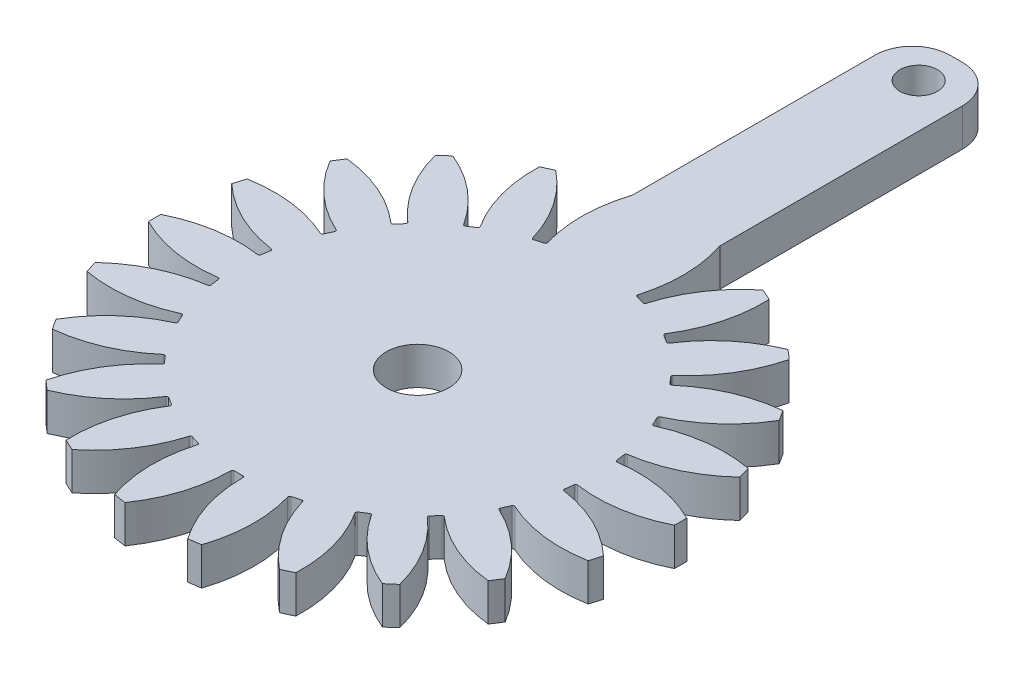
SolidWorks part; units mm, degrees
material "Copper"
ref_plane "Front Plane" through (0, 0, 0) normal (0, 0, 1) x (1, 0, 0)
ref_plane "Top Plane" through (0, 0, 0) normal (0, 1, 0) x (1, 0, 0)
ref_plane "Right Plane" through (0, 0, 0) normal (1, 0, 0) x (0, 0, -1)
sketch "Sketch1" plane through (0, 0, 0) normal (0, 1, 0) x (1, 0, 0)
  circle A0 centre (0, 0) radius 21
  dimension "D1" = 42
extrude "Boss-Extrude1" add sketch "Sketch1" along normal blind 3
sketch "Sketch2" plane through (0, 3, 0) normal (0, 1, 0) x (1, 0, 0)
  circle A0 centre (0, 0) radius 2.5
  dimension "D1" = 5
extrude "Cut-Extrude1" cut sketch "Sketch2" against normal through all both and the other way through all
sketch "Sketch3" plane through (0, 3, 0) normal (0, 1, 0) x (1, 0, 0)
  line L0 (0, 0) -> (0, 21) construction
  line L1 (0.35, 14.3) -> (-0.35, 14.3)
  circle A0 centre (0, 0) radius 21 construction
  arc A3 (-2.5, 20.8507) -> (2.5, 20.8507) centre (0, 0) cw
  arc A6 (-0.35, 14.3) -> (-0.4765, 14.4265) centre (-0.35, 14.4265) cw
  arc A7 (-0.4765, 14.4265) -> (-2.5, 20.8507) centre (-11.6858, 14.4265) ccw
  arc A8 (0.35, 14.3) -> (0.4765, 14.4265) centre (0.35, 14.4265) ccw
  arc A9 (0.4765, 14.4265) -> (2.5, 20.8507) centre (11.6858, 14.4265) cw
  point P21 (0, 21)
  point P22 (0, 14.3)
  dimension "D4" = 6.7
  dimension "D1" = 5
  dimension "D2" = 0.7
extrude "Cut-Extrude2" cut sketch "Sketch3" against normal through all both and the other way through all
pattern_circular "CirPattern1" count 22 over 360 about axis through (0, 0, 0) along (0, 1, 0) of "Cut-Extrude2"
sketch "Sketch4" plane through (0, 3, 0) normal (0, 1, 0) x (1, 0, 0)
  line L0 (0, 27.75) -> (0, 0) construction
  line L1 (-3.5, 43) -> (3.5, 43)
  line L2 (-3.5, 43) -> (-3.5, 12.5)
  line L3 (-3.5, 12.5) -> (3.5, 12.5)
  line L4 (3.5, 43) -> (3.5, 12.5)
  line L5 (-3.5, 43) -> (3.5, 12.5) construction
  line L6 (-3.5, 12.5) -> (3.5, 43) construction
  point P0 (0, 27.75)
  dimension "D1" = 7
  dimension "D2" = 30.5
  dimension "D3" = 12.5
extrude "Boss-Extrude2" add sketch "Sketch4" against normal blind 3
fillet "Fillet1" radius 3 2 edges at (3.5, 1.5, -43) (-3.5, 1.5, -43)
sketch "Sketch5" plane through (0, 3, 0) normal (0, 1, 0) x (1, 0, 0)
  line L0 (0, 43) -> (0, 40) construction
  line L1 (0.5, 43) -> (-0.5, 43) construction
  circle A0 centre (0, 40) radius 1.5
  dimension "D2" = 3
  dimension "D1" = 3
extrude "Cut-Extrude3" cut sketch "Sketch5" against normal through all both and the other way through all
sketch "Sketch6" plane through (0, 3, 0) normal (0, 1, 0) x (1, 0, 0)
  line L0 (0.5, 43) -> (-0.5, 43) construction
  line L1 (0, 0) -> (0, 43) construction
